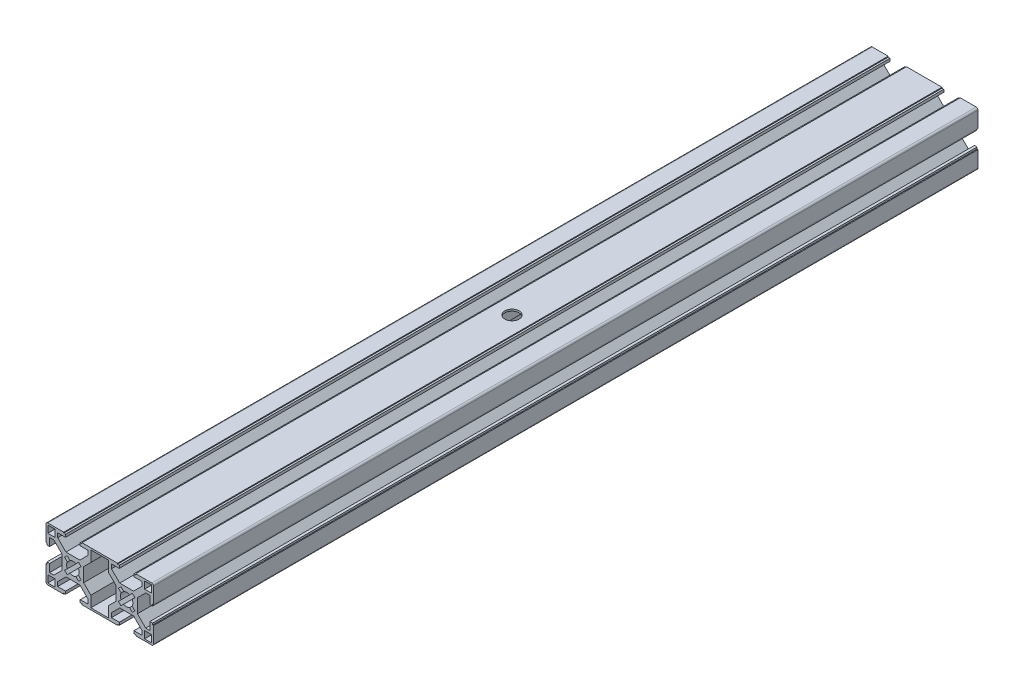
SolidWorks part; units mm, degrees
material "6063-T83"
ref_plane "Plano frontal" through (0, 0, 0) normal (0, 0, 1) x (1, 0, 0)
ref_plane "Plano superior" through (0, 0, 0) normal (0, 1, 0) x (1, 0, 0)
ref_plane "Plano direito" through (0, 0, 0) normal (1, 0, 0) x (0, 0, -1)
sketch "Esboço1" plane through (0, 0, 0) normal (0, 0, 1) x (1, 0, 0)
  line L5 (0, 0) -> (-17.7944, 17.7944) construction
  line L6 (0, 3.5) -> (0, 6)
  line L8 (0, 6) -> (-3.8787, 6)
  line L9 (-3.5, 0) -> (-6, 0)
  line L48 (-6, 0) -> (-6, 3.8787)
  line L49 (-3.8787, 6) -> (-8.5, 10.6213)
  line L50 (-6, 3.8787) -> (-10.6213, 8.5)
  line L51 (0, 0) -> (-12.921, 0) construction
  line L52 (-8.5, 13) -> (-4.1, 13)
  line L53 (-4.1, 13) -> (-4.1, 14.5)
  line L54 (-4.1, 14.5) -> (-5.1, 14.5)
  line L55 (-5.1, 14.5) -> (-5.1, 15)
  line L56 (-5.1, 15) -> (-15, 15)
  line L57 (-15, 5.1) -> (-15, 15)
  line L58 (-14.5, 5.1) -> (-15, 5.1)
  line L59 (-14.5, 4.1) -> (-14.5, 5.1)
  line L60 (-13, 4.1) -> (-14.5, 4.1)
  line L61 (-13, 8.5) -> (-13, 4.1)
  line L62 (-1.6646, 3.0788) -> (-3.182, 4.5962)
  line L63 (-3.0788, 1.6646) -> (-4.5962, 3.182)
  line L64 (-4.5962, 3.182) -> (-3.182, 4.5962)
  line L65 (-8.5, 13) -> (-8.5, 10.6213)
  line L66 (-10, 14) -> (-14, 14)
  line L67 (-10, 14) -> (-10, 10)
  line L68 (-10, 10) -> (-14, 10)
  line L69 (-14, 14) -> (-14, 10)
  line L70 (-10, 14) -> (-14, 10) construction
  line L71 (-10, 10) -> (-14, 14) construction
  line L72 (-13, 8.5) -> (-10.6213, 8.5)
  circle A1 centre (0, 0) radius 3.5
  point P25 (-12, 12)
  dimension "D5" = 10.9
  dimension "D9" = 5.5
  dimension "D10" = 2
  dimension "D11" = 4
  dimension "D12" = 4
  dimension "D13" = 1
  dimension "D1" = 7
  dimension "D2" = 6
  dimension "D3" = 3
  dimension "D4" = 9.9
  dimension "D6" = 0.5
  dimension "D7" = 1.5
  dimension "D8" = 15
  dimension "D14" = 6.5
extrude "Ressalto-extrusão1" add sketch "Esboço1" along normal blind 460 contours A1 L6 L8 L49 L65 L52 L53 L54 L55 L56 L57 L58 L59 L60 L61 L72 L50 L48 L9 L63 L64 L62 L69 L66 L67 L68
sketch "Esboço3" plane through (0, 0, 0) normal (1, 0, 0) x (0, 0, -1)
  line L0 (0, 0) -> (-1000, 0) construction
  dimension "D1" = 1000
pattern_circular "PadrãoCircular1" count 4 over 360 about axis through (0, 0, 0) along (0, 0, 1) of "Ressalto-extrusão1"
pattern_linear "Padrão linear1" count 2 spacing 30 along (1, 0, 0) of "Ressalto-extrusão1", "PadrãoCircular1"
sketch "Esboço4" plane through (0, 0, 0) normal (0, 0, -1) x (-1, 0, 0)
  line L0 (-20, 14) -> (-20, -14)
  line L1 (-20, -14) -> (-10, -14)
  line L2 (-10, -14) -> (-10, 14)
  line L3 (-10, 14) -> (-20, 14)
extrude "Corte-extrusão1" cut sketch "Esboço4" against normal through all
fillet "Filete1" radius 1 4 edges at (45, -15, 230) (45, 15, 230) (-15, 15, 230) (-15, -15, 230)
sketch "Esboço5" plane through (0, 15, 0) normal (0, 1, 0) x (1, 0, 0)
  line L0 (15, 0) -> (15, -460) construction
  line L1 (5.1, 0) -> (24.9, 0) construction
  line L2 (5.1, -460) -> (24.9, -460) construction
  circle A0 centre (15, -230) radius 4
  dimension "D1" = 8
extrude "Corte-extrusão2" cut sketch "Esboço5" against normal through all
ref_plane "Plane1" through (0, 0, 230) normal (0, 0, -1) x (-1, 0, 0)
